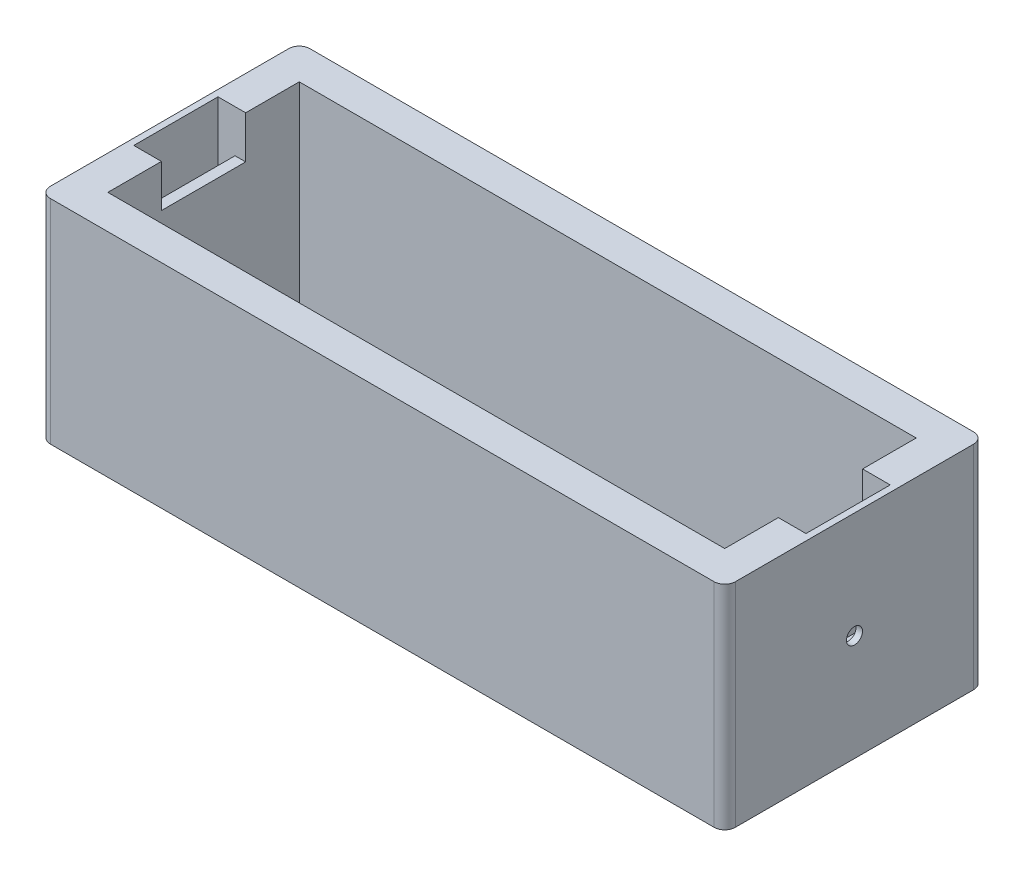
SolidWorks part; units mm, degrees
ref_plane "Front Plane" through (0, 0, 0) normal (0, 0, 1) x (1, 0, 0)
ref_plane "Top Plane" through (0, 0, 0) normal (0, 1, 0) x (1, 0, 0)
ref_plane "Right Plane" through (0, 0, 0) normal (1, 0, 0) x (0, 0, -1)
sketch "Sketch2" plane through (0, 0, 0) normal (0, 1, 0) x (1, 0, 0)
  line L1 (-32.2, -12.2) -> (32.2, -12.2)
  line L2 (-32.2, -12.2) -> (-32.2, 12.2)
  line L3 (-32.2, 12.2) -> (32.2, 12.2)
  line L4 (32.2, -12.2) -> (32.2, 12.2)
  line L5 (-32.2, -12.2) -> (32.2, 12.2) construction
  line L6 (-32.2, 12.2) -> (32.2, -12.2) construction
  point P0 (0, 0)
  dimension "D1" = 64.4
  dimension "D2" = 24.4
extrude "Boss-Extrude1" add sketch "Sketch2" along normal blind 20
sketch "Sketch3" plane through (0, 20, 0) normal (0, 1, 0) x (1, 0, 0)
  line L0 (32.2, -12.2) -> (32.2, 12.2) construction
  line L1 (-29, 9) -> (29, 9)
  line L2 (-29, 9) -> (-29, -9)
  line L3 (-29, -9) -> (29, -9)
  line L4 (29, 9) -> (29, -9)
  line L5 (-29, 9) -> (29, -9) construction
  line L6 (-29, -9) -> (29, 9) construction
  line L7 (-32.2, -12.2) -> (32.2, -12.2) construction
  point P0 (0, 0)
  dimension "D1" = 3.2
  dimension "D2" = 3.2
extrude "Cut-Extrude1" cut sketch "Sketch3" against normal offset from surface (18 mm away) 2 up to face at (0, 0, 0)
fillet "Fillet1" radius 1 4 edges at (-32.2, 10, -12.2) (32.2, 10, -12.2) (32.2, 10, 12.2) (-32.2, 10, 12.2)
sketch "Sketch4" plane through (0, 20, 0) normal (0, 1, 0) x (1, 0, 0)
  line L0 (-29, 9) -> (-29, -9) construction
  line L1 (-29, 0) -> (-30, 0)
  line L2 (-29, 0) -> (-29, 3.96)
  line L3 (-29, 3.96) -> (-30, 3.96)
  line L4 (-30, 0) -> (-30, 3.96)
  dimension "D1" = 1
  dimension "D2" = 3.96
extrude "Cut-Extrude2" cut sketch "Sketch4" against normal offset from surface (4 mm away) 4 up to face at (0, 20, 0)
sketch "Sketch5" plane through (0, 20, 0) normal (0, 1, 0) x (1, 0, 0)
  line L1 (-30, 0) -> (-31.6, 0)
  line L2 (-30, 0) -> (-30, 3.96)
  line L3 (-30, 3.96) -> (-31.6, 3.96)
  line L4 (-31.6, 0) -> (-31.6, 3.96)
  dimension "D2" = 3.96
  dimension "D1" = 1.6
extrude "Cut-Extrude3" cut sketch "Sketch5" against normal offset from surface (12 mm away) 12 up to face at (-14.75, 20, -0.99)
mirror "Mirror4" about plane through (0, 0, 0) normal (1, 0, 0) of "Cut-Extrude3", "Cut-Extrude2"
mirror "Mirror5" about plane through (0, 0, 0) normal (0, 0, 1) of "Mirror4", "Cut-Extrude2", "Cut-Extrude3"
sketch "Sketch6" plane through (32.2, 0, 0) normal (1, 0, 0) x (0, 0, -1)
  line L0 (-11.2, 0) -> (11.2, 0) construction
  circle A0 centre (0, 10) radius 0.75
  dimension "D1" = 1.5
  dimension "D2" = 10
extrude "Cut-Extrude4" cut sketch "Sketch6" against normal up to next
mirror "Mirror6" about plane through (0, 0, 0) normal (1, 0, 0) of "Cut-Extrude4"
equation "\"D1@Sketch2\"= 50 + 6.4 + 8"
equation "\"D2@Sketch2\" = 14 + 6.4 + 4"
equation "\"D1@Boss-Extrude1\"= 14 + 2 + 4"
equation "\"D1@Sketch3\"=3.2"
equation "\"D2@Sketch3\"=3.2"
equation "\"D1@Cut-Extrude1\"=2"
equation "\"D1@Fillet1\"=1"
equation "\"D2@Sketch4\"=7.92 / 2"
equation "\"D1@Sketch5\"=1.6"
equation "\"D2@Sketch5\"=7.92 / 2"
